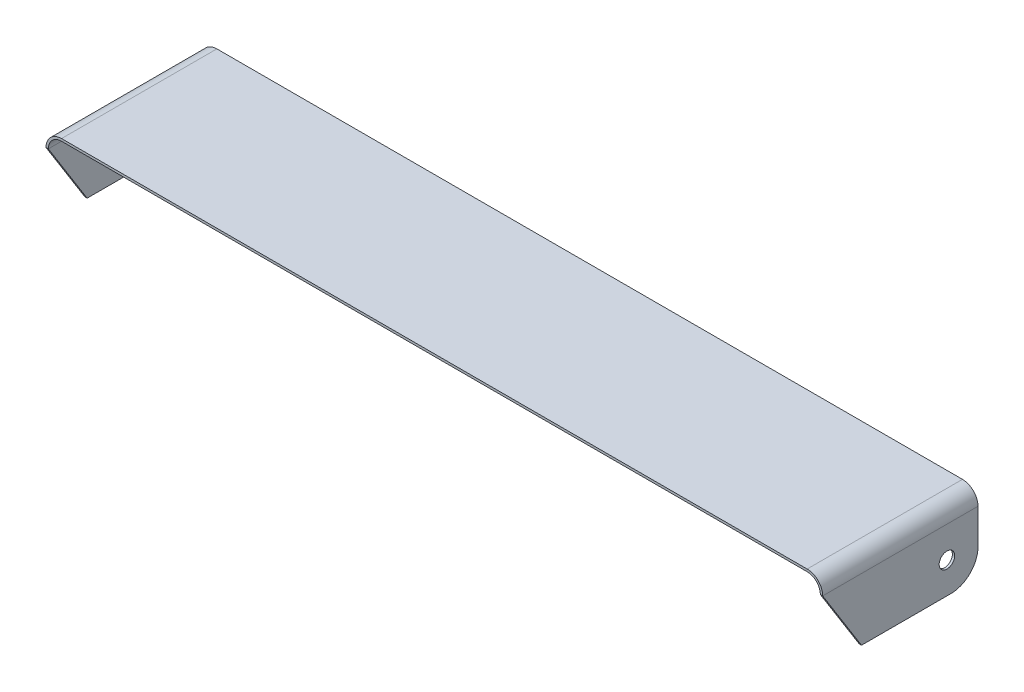
SolidWorks part; units mm, degrees
ref_plane "Płaszczyzna przednia" through (0, 0, 0) normal (0, 0, 1) x (1, 0, 0)
ref_plane "Płaszczyzna górna" through (0, 0, 0) normal (0, 1, 0) x (1, 0, 0)
ref_plane "Płaszczyzna prawa" through (0, 0, 0) normal (1, 0, 0) x (0, 0, -1)
sketch "Szkic1" plane through (0, 0, 0) normal (0, 0, 1) x (1, 0, 0)
  line L0 (-500, 0) -> (-500, 80)
  line L1 (-480, 100) -> (480, 100)
  line L2 (500, 80) -> (500, 0)
  line L3 (-497, 0) -> (-497, 80)
  line L4 (-480, 97) -> (480, 97)
  line L5 (497, 80) -> (497, 0)
  line L6 (-500, 0) -> (-497, 0)
  line L7 (497, 0) -> (500, 0)
  arc A0 (480, 100) -> (500, 80) centre (480, 80) cw
  arc A1 (-500, 80) -> (-480, 100) centre (-480, 80) cw
  arc A2 (-497, 80) -> (-480, 97) centre (-480, 80) cw
  arc A3 (480, 97) -> (497, 80) centre (480, 80) cw
  point P8 (500, 100)
  point P11 (-500, 100)
  dimension "D4" = 20
  dimension "D1" = 1000
  dimension "D2" = 100
  dimension "D3" = 500
  dimension "D5" = 3
extrude "Dodanie-wyciągnięcie1" add sketch "Szkic1" along normal mid plane 200
sketch "Szkic2" plane through (500, 0, 0) normal (1, 0, 0) x (0, 0, -1)
  line L0 (-100, 80) -> (-100, 0)
  line L1 (-100, 0) -> (-50, 0)
  line L2 (-100, 0) -> (100, 0) construction
  line L3 (-50, 0) -> (-100, 80)
  dimension "D1" = 80
  dimension "D2" = 50
extrude "Wytnij-wyciągnięcie1" cut sketch "Szkic2" against normal through all
sketch "Szkic3" plane through (-500, 0, 0) normal (-1, 0, 0) x (0, 0, 1)
  line L0 (100, 100) -> (-100, 100) construction
  line L1 (-100, 80) -> (-100, 0) construction
  circle A0 centre (-60, 40) radius 10
  dimension "D3" = 20
  dimension "D1" = 60
  dimension "D2" = 40
extrude "Wytnij-wyciągnięcie2" cut sketch "Szkic3" against normal through all
fillet "Zaokrąglenie1" radius 35 2 edges at (-498.5, 0, -100) (498.5, 0, -100)
